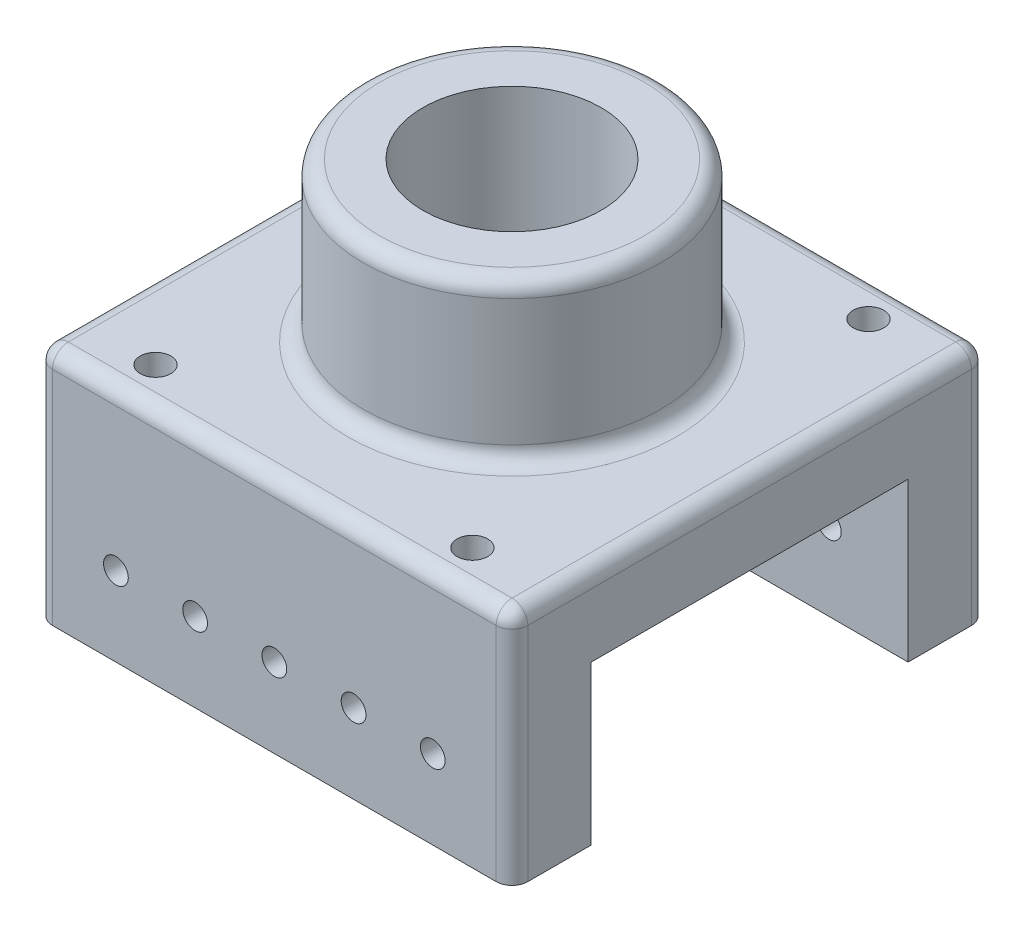
SolidWorks part; units mm, degrees
ref_plane "Front" through (0, 0, 0) normal (0, 0, 1) x (1, 0, 0)
ref_plane "Top" through (0, 0, 0) normal (0, 1, 0) x (1, 0, 0)
ref_plane "Right" through (0, 0, 0) normal (1, 0, 0) x (0, 0, -1)
sketch "Sketch1"
sketch_block_instance "Block1-1"
sketch_block "Block1" parameters "D1"=127, "D2"=50.8
sketch "Sketch2" plane through (0, 0, 0) normal (0, 1, 0) x (1, 0, 0)
  line L0 (-63.5, 25.4) -> (63.5, 25.4) construction
  line L1 (-38.1, 38.1) -> (38.1, 38.1)
  line L2 (-38.1, 38.1) -> (-38.1, -38.1)
  line L3 (-38.1, -38.1) -> (38.1, -38.1)
  line L4 (38.1, 38.1) -> (38.1, -38.1)
  line L5 (-38.1, 38.1) -> (38.1, -38.1) construction
  line L6 (-38.1, -38.1) -> (38.1, 38.1) construction
  circle A0 centre (0, 0) radius 14.2875
  point P0 (0, 0)
  dimension "D2" = 28.575
  dimension "D1" = 76.2
  dimension "D3" = 12.7
  dimension "D4" = 76.2
extrude "Boss-Extrude1" add sketch "Sketch2" along normal blind 12.7
sketch "Sketch3" plane through (0, 12.7, 0) normal (0, 1, 0) x (1, 0, 0)
  line L4 (38.1, -38.1) -> (38.1, 38.1)
  line L5 (38.1, 38.1) -> (-38.1, 38.1)
  line L6 (-38.1, 38.1) -> (-38.1, -38.1)
  line L7 (-38.1, -38.1) -> (38.1, -38.1)
  line L8 (38.1, -38.1) -> (38.1, 38.1)
  line L9 (38.1, 38.1) -> (-38.1, 38.1)
  line L10 (-38.1, 38.1) -> (-38.1, -38.1)
  line L11 (-38.1, -38.1) -> (38.1, -38.1)
  circle A0 centre (0, 0) radius 14.2875 construction
  circle A1 centre (0, 0) radius 14.2875
  circle A2 centre (0, 0) radius 23.8125
  circle M9 centre (0, 0) radius 14.2875
  dimension "D1" = 0
  dimension "D2" = 9.525
extrude "Boss-Extrude2" add sketch "Sketch3" along normal blind 25.4 contours A2 M9
sketch "Sketch4" plane through (0, 0, 0) normal (0, -1, 0) x (1, 0, 0)
  line L0 (-63.5, -25.4) -> (63.5, -25.4) construction
  line L1 (38.1, -25.4) -> (-38.1, -25.4)
  line L2 (38.1, -25.4) -> (38.1, -38.1)
  line L3 (38.1, -38.1) -> (-38.1, -38.1)
  line L4 (-38.1, -25.4) -> (-38.1, -38.1)
  line L5 (38.1, 38.1) -> (38.1, -38.1) construction
  line L6 (-63.5, 25.4) -> (63.5, 25.4) construction
  line L7 (38.1, 25.4) -> (-38.1, 25.4)
  line L8 (38.1, 25.4) -> (38.1, 38.1)
  line L9 (38.1, 38.1) -> (-38.1, 38.1)
  line L10 (-38.1, 25.4) -> (-38.1, 38.1)
  line L11 (-38.1, -38.1) -> (-38.1, 38.1) construction
  line L12 (-38.1, 38.1) -> (38.1, 38.1) construction
extrude "Boss-Extrude3" add sketch "Sketch4" along normal blind 25.4
hole_wizard "#10 (0.1935) Diameter Hole1" positions "Sketch5" profile "Sketch6" hole size "#10" standard "ANSI Inch" end condition through all
sketch "Sketch5" plane through (0, -25.4, 0) normal (0, -1, 0) x (-1, 0, 0)
  line L0 (-38.1, 31.75) -> (38.1, 31.75) construction
  line L1 (-38.1, 38.1) -> (-38.1, 25.4) construction
  line L2 (38.1, 25.4) -> (38.1, 38.1) construction
  line L5 (0, 38.1) -> (0, 25.4) construction
  line L6 (38.1, 38.1) -> (-38.1, 38.1) construction
  line L7 (63.5, 25.4) -> (-63.5, 25.4) construction
  line L8 (-38.1, 0) -> (38.1, 0) construction
  line L9 (-38.1, -25.4) -> (-38.1, 25.4) construction
  line L10 (38.1, 25.4) -> (38.1, -25.4) construction
  point P17 (-25.4, 31.75)
  point P19 (25.4, 31.75)
  point P28 (25.4, -31.75)
  point P29 (-25.4, -31.75)
  dimension "D1" = 50.8
sketch "Sketch6" plane through (25.4, -25.4, -31.75) normal (1, 0, 0) x (0, 0, -1)
  line L0 (0, 0) -> (0, 63.5)
  line L1 (0, 63.5) -> (2.4574, 63.5)
  line L2 (2.4574, 63.5) -> (2.4574, 0)
  line L5 (2.4574, 0) -> (0, 0)
  line L11 (0, -6.35) -> (0, 107.95) construction
  dimension "Thru Hole Dia." = 4.9149
  dimension "Thru Hole Depth" = 63.5
fillet "Fillet1" radius 2.54 6 edges at (38.1, -6.35, 38.1) (-38.1, -6.35, 38.1) (-38.1, -6.35, -38.1) (38.1, -6.35, -38.1) (0, 12.7, 23.8125) (0, 38.1, 23.8125)
fillet "Fillet2" radius 2.54 8 edges at (37.3561, 12.7, -37.3561) (38.1, 12.7, 0) (37.3561, 12.7, 37.3561) (0, 12.7, 38.1) (-37.3561, 12.7, 37.3561) (-38.1, 12.7, 0) (-37.3561, 12.7, -37.3561) (0, 12.7, -38.1)
hole_wizard "5/32 (0.15625) Diameter Hole1" positions "Sketch7" profile "Sketch8" hole size "5/32" standard "ANSI Inch" end condition through all
sketch "Sketch7" plane through (0, 0, -38.1) normal (0, 0, -1) x (-1, 0, 0)
  line L1 (0, -25.4) -> (0, -12.7) construction
  line L2 (35.56, -25.4) -> (-35.56, -25.4) construction
  point P4 (0, -12.7)
  point P15 (12.7, -12.7)
  point P16 (25.4, -12.7)
  point P20 (-12.7, -12.7)
  point P21 (-25.4, -12.7)
  dimension "D1" = 12.7
  dimension "D2" = 3
  dimension "D3" = 3
sketch "Sketch8" plane through (0, -12.7, -38.1) normal (1, 0, 0) x (0, 1, 0)
  line L0 (0, 0) -> (0, 76.2)
  line L1 (0, 76.2) -> (1.9844, 76.2)
  line L2 (1.9844, 76.2) -> (1.9844, 0)
  line L5 (1.9844, 0) -> (0, 0)
  line L11 (0, -6.35) -> (0, 107.95) construction
  dimension "Thru Hole Dia." = 3.9688
  dimension "Thru Hole Depth" = 76.2
